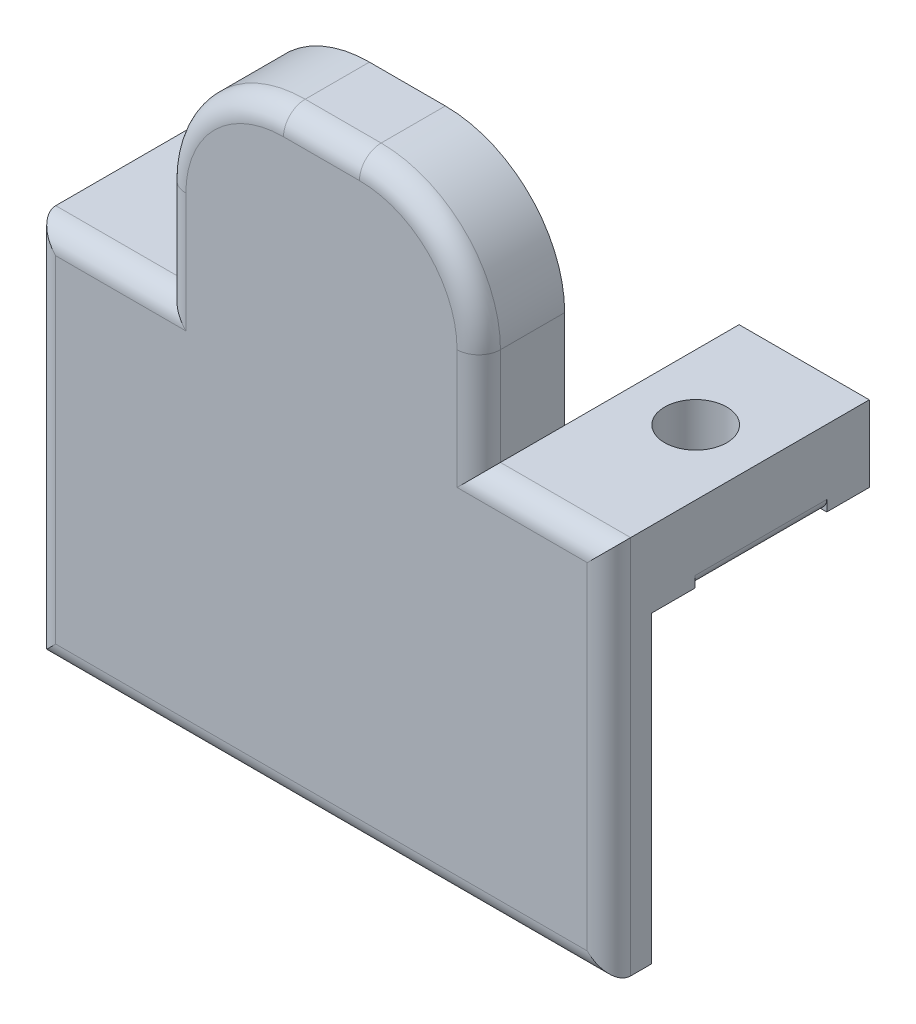
SolidWorks part; units mm, degrees
ref_plane "정면" through (0, 0, 0) normal (0, 0, 1) x (1, 0, 0)
ref_plane "윗면" through (0, 0, 0) normal (0, 1, 0) x (1, 0, 0)
ref_plane "우측면" through (0, 0, 0) normal (1, 0, 0) x (0, 0, -1)
sketch "스케치1" plane through (0, 0, 0) normal (0, 0, 1) x (1, 0, 0)
  line L1 (-26.5, 17.5) -> (26.5, 17.5)
  line L2 (-26.5, 17.5) -> (-26.5, -17.5)
  line L3 (-26.5, -17.5) -> (26.5, -17.5)
  line L4 (26.5, 17.5) -> (26.5, -17.5)
  line L5 (-26.5, 17.5) -> (26.5, -17.5) construction
  line L6 (-26.5, -17.5) -> (26.5, 17.5) construction
  point P0 (0, 0)
  dimension "D1" = 35
  dimension "D2" = 53
extrude "보스-돌출1" add sketch "스케치1" along normal blind 3.92
sketch "스케치2" plane through (0, 0, 3.92) normal (0, 0, 1) x (1, 0, 0)
  line L0 (26.5, 17.5) -> (-26.5, 17.5) construction
  line L1 (-26.5, 17.5) -> (-14.5, 17.5)
  line L2 (-26.5, 17.5) -> (-26.5, -9.5)
  line L3 (-26.5, -9.5) -> (-14.5, -9.5)
  line L4 (-14.5, 17.5) -> (-14.5, -9.5)
  line L5 (14.5, 17.5) -> (26.5, 17.5)
  line L6 (14.5, 17.5) -> (14.5, -9.5)
  line L7 (14.5, -9.5) -> (26.5, -9.5)
  line L8 (26.5, 17.5) -> (26.5, -9.5)
  line L9 (26.5, -17.5) -> (26.5, 17.5) construction
  dimension "D1" = 27
  dimension "D2" = 12
  dimension "D3" = 12
  dimension "D4" = 27
extrude "컷-돌출1" cut sketch "스케치2" against normal blind 4
sketch "스케치3" plane through (0, 0, 0) normal (0, 0, -1) x (-1, 0, 0)
  line L0 (0, 11) -> (0, -11) construction
  line L1 (-14.5, -9.5) -> (-26.5, -9.5)
  line L2 (-14.5, -9.5) -> (-14.5, -2.5)
  line L3 (-14.5, -2.5) -> (-26.5, -2.5)
  line L4 (-26.5, -9.5) -> (-26.5, -2.5)
  line L5 (26.5, -9.5) -> (26.5, -2.5)
  line L6 (14.5, -2.5) -> (26.5, -2.5)
  line L7 (14.5, -9.5) -> (14.5, -2.5)
  line L8 (14.5, -9.5) -> (26.5, -9.5)
  dimension "D1" = 12
  dimension "D2" = 7
extrude "보스-돌출2" add sketch "스케치3" along normal blind 16.08 and the other way through all
sketch "스케치4" plane through (0, -9.5, 0) normal (0, -1, 0) x (1, 0, 0)
  line L0 (-14.5, 0) -> (-14.5, -16.08) construction
  line L1 (-26.5, -16.08) -> (-14.5, -16.08)
  line L2 (-26.5, -16.08) -> (-26.5, -12.16)
  line L3 (-26.5, -12.16) -> (-14.5, -12.16)
  line L4 (-14.5, -16.08) -> (-14.5, -12.16)
  line L5 (26.5, -16.08) -> (14.5, -16.08) construction
  line L6 (14.5, -16.08) -> (26.5, -16.08)
  line L7 (14.5, -16.08) -> (14.5, -12.16)
  line L8 (14.5, -12.16) -> (26.5, -12.16)
  line L9 (26.5, -16.08) -> (26.5, -12.16)
  line L10 (26.5, 0) -> (26.5, -16.08) construction
  dimension "D1" = 3.92
  dimension "D2" = 3.92
extrude "보스-돌출3" add sketch "스케치4" along normal blind 8
sketch "스케치5" plane through (0, -2.5, 0) normal (0, 1, 0) x (1, 0, 0)
  line L0 (-26.5, -3.92) -> (-26.5, 16.08) construction
  line L1 (-26.5, -3.92) -> (-14.5, -3.92) construction
  line L2 (0, -11) -> (0, 11) construction
  circle A0 centre (-20.5, 6.08) radius 2.86
  circle A1 centre (20.5, 6.08) radius 2.86
  dimension "D2" = 5.72
  dimension "D1" = 6
  dimension "D3" = 10
extrude "컷-돌출2" cut sketch "스케치5" against normal through all
sketch "스케치7" plane through (0, 0, 3.92) normal (0, 0, 1) x (1, 0, 0)
  line L0 (-14.5, -2.5) -> (-26.5, -2.5)
  line L1 (-26.5, -2.5) -> (-26.5, -17.5)
  line L2 (-26.5, -17.5) -> (26.5, -17.5)
  line L3 (26.5, -17.5) -> (26.5, -2.5)
  line L4 (26.5, -2.5) -> (14.5, -2.5)
  line L5 (14.5, -2.5) -> (14.5, 17.5)
  line L6 (14.5, 17.5) -> (-14.5, 17.5)
  line L7 (-14.5, 17.5) -> (-14.5, -2.5)
extrude "보스-돌출4" add sketch "스케치7" along normal blind 4
sketch "스케치8" plane through (0, -17.5, 0) normal (0, -1, 0) x (1, 0, 0)
  line L0 (26.5, 7.92) -> (26.5, 0) construction
  line L1 (-26.5, 7.92) -> (26.5, 7.92)
  line L2 (-26.5, 7.92) -> (-26.5, 4)
  line L3 (-26.5, 4) -> (26.5, 4)
  line L4 (26.5, 7.92) -> (26.5, 4)
  dimension "D1" = 3.92
extrude "보스-돌출5" add sketch "스케치8" along normal blind 20
fillet "필렛1" radius 2.5 2 edges at (14.5, -9.5, -6.08) (-14.5, -9.5, -6.08)
fillet "필렛2" radius 11 2 edges at (14.5, 17.5, 3.96) (-14.5, 17.5, 3.96)
fillet "필렛3" radius 1 2 edges at (-26.5, -9.5, -6.08) (26.5, -9.5, -6.08)
fillet "필렛4" radius 2 10 edges at (20.5, -2.5, 7.92) (26.5, -20, 7.92) (0, -37.5, 7.92) (-26.5, -20, 7.92) (-20.5, -2.5, 7.92) (-14.5, 2, 7.92) (-11.2782, 14.2782, 7.92) (0, 17.5, 7.92) (11.2782, 14.2782, 7.92) (14.5, 2, 7.92)
sketch "스케치9" plane through (26.5, 0, 0) normal (1, 0, 0) x (0, 0, -1)
  line L0 (16.08, -2.5) -> (16.08, -17.5) construction
  line L1 (16.08, -17.5) -> (-4, -17.5)
  line L2 (16.08, -17.5) -> (16.08, -9.5)
  line L3 (16.08, -9.5) -> (-4, -9.5)
  line L4 (-4, -17.5) -> (-4, -9.5)
  line L5 (12.16, -9.5) -> (0, -9.5) construction
  point P8 (-4, -17.5)
  dimension "D1" = 0
extrude "컷-돌출5" cut sketch "스케치9" against normal through all
sketch "스케치6" plane through (0, 0, 0) normal (0, 0, 1) x (1, 0, 0)
  line L2 (-3.5, 17.5) -> (3.5, 17.5) construction
  line L4 (-14.5, -2.5) -> (-14.5, 6.5) construction
  circle A0 centre (0, 2.5) radius 6
  point P6 (-11.3861, 0.4203)
  dimension "D3" = 12
  dimension "D1" = 15
  dimension "D2" = 14.5
extrude "컷-돌출3" cut sketch "스케치6" along normal blind 6.5
